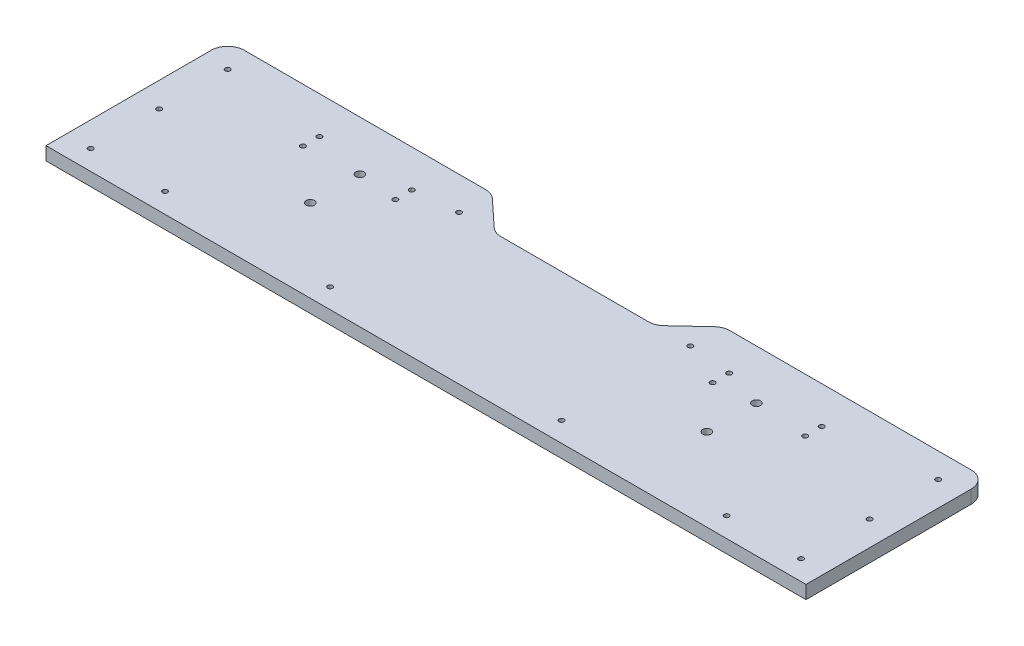
SolidWorks part; units mm, degrees
ref_plane "前视基准面" through (0, 0, 0) normal (0, 0, 1) x (1, 0, 0)
ref_plane "上视基准面" through (0, 0, 0) normal (0, 1, 0) x (1, 0, 0)
ref_plane "右视基准面" through (0, 0, 0) normal (1, 0, 0) x (0, 0, -1)
sketch "草图2" plane through (0, 0, 0) normal (0, 1, 0) x (1, 0, 0)
  line L1 (-230, 55) -> (230, 55)
  line L2 (-230, 55) -> (-230, -55)
  line L3 (-230, -55) -> (230, -55)
  line L4 (230, 55) -> (230, -55)
  line L5 (-230, 55) -> (230, -55) construction
  line L6 (-230, -55) -> (230, 55) construction
  point P0 (0, 0)
  dimension "D1" = 460
  dimension "D2" = 110
extrude "凸台-拉伸1" add sketch "草图2" along normal blind 8
sketch "草图3" plane through (0, 8, 0) normal (0, 1, 0) x (1, 0, 0)
  line L0 (-70, 55) -> (-48.5526, 35)
  line L1 (230, 55) -> (-230, 55) construction
  line L2 (-48.5526, 35) -> (48.5526, 35)
  line L3 (48.5526, 35) -> (70, 55)
  line L4 (70, 55) -> (-70, 55)
  line L5 (-230, 55) -> (-230, -55) construction
  line L7 (-230, -55) -> (230, -55) construction
  circle A0 centre (-120, 25) radius 2.5
  circle A2 centre (-120, -5) radius 2.5
  circle A3 centre (-152, 32.5) radius 1.5
  circle A4 centre (-152, 22.5) radius 1.5
  circle A5 centre (-96, 32.5) radius 1.5
  circle A6 centre (-96, 22.5) radius 1.5
  point P24 (0, 0)
  point P25 (0, 0)
  point P27 (-99.4233, 55)
  dimension "D6" = 110
  dimension "D9" = 78
  dimension "D12" = 24
  dimension "D1" = 20
  dimension "D2" = 43
  dimension "D3" = 43
  dimension "D4" = 160
  dimension "D5" = 160
  dimension "D7" = 50
  dimension "D8" = 30
  dimension "D10" = 22.5
  dimension "D11" = 10
sketch "草图4" plane through (0, 8, 0) normal (0, 1, 0) x (1, 0, 0)
  line L0 (-230, -55) -> (230, -55) construction
  line L1 (230, 55) -> (-230, 55) construction
  line L3 (-230, 55) -> (-230, -55) construction
  circle A0 centre (-70, 35) radius 1.5
  circle A1 centre (-70, -43) radius 1.5
  circle A2 centre (-215, -43) radius 1.5
  circle A3 centre (-215, 40) radius 1.5
  circle A5 centre (-170, -43) radius 1.5
  circle A6 centre (-215, -1.5) radius 1.5
  point P12 (0, 0)
  point P19 (-230, 39.9576)
  point P22 (-48.5526, 35)
  dimension "D1" = 12
  dimension "D2" = 15
  dimension "D3" = 15
  dimension "D4" = 41.5
  dimension "D5" = 20
  dimension "D6" = 160
  dimension "D7" = 45
extrude "切除-拉伸1" cut sketch "草图4" against normal through all
extrude "切除-拉伸2" cut sketch "草图3" against normal through all
mirror "镜向1" about plane through (0, 0, 0) normal (1, 0, 0) of "切除-拉伸1", "切除-拉伸2"
fillet "圆角1" radius 10 6 edges at (-230, 4, -55) (230, 4, -55) (70, 4, -55) (48.5526, 4, -35) (-48.5526, 4, -35) (-70, 4, -55)
